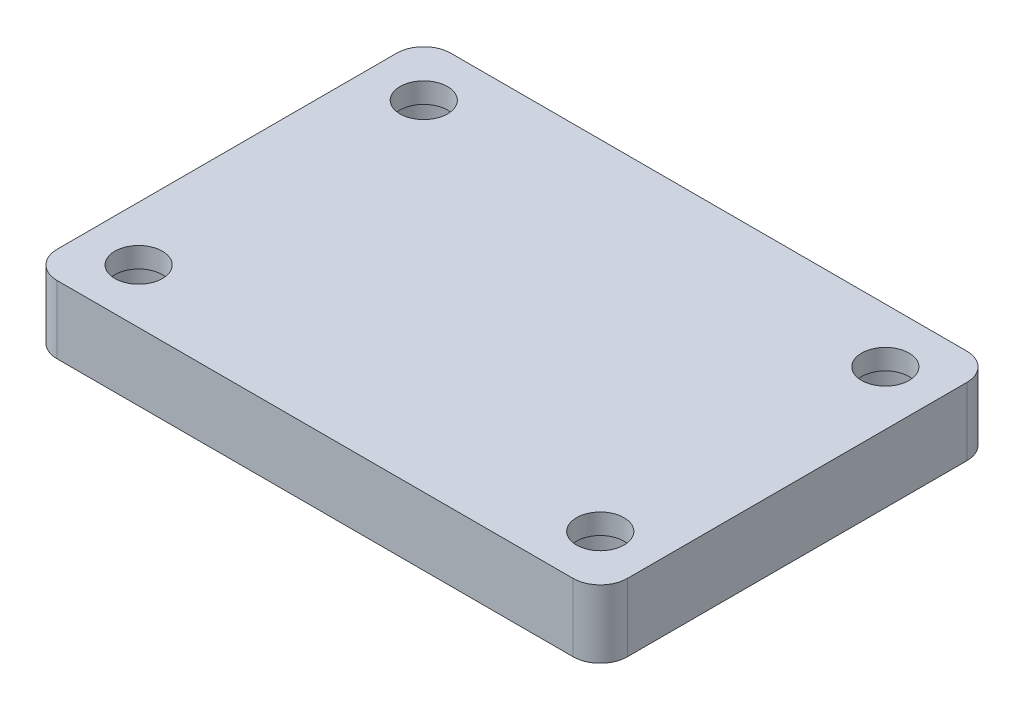
SolidWorks part; units mm, degrees
material "Plain Carbon Steel"
ref_plane "Front Plane" through (0, 0, 0) normal (0, 0, 1) x (1, 0, 0)
ref_plane "Top Plane" through (0, 0, 0) normal (0, 1, 0) x (1, 0, 0)
ref_plane "Right Plane" through (0, 0, 0) normal (1, 0, 0) x (0, 0, -1)
sketch "Sketch1" plane through (0, 0, 0) normal (0, 1, 0) x (1, 0, 0)
  line L1 (0, 0) -> (84, 0)
  line L2 (0, 0) -> (0, 58)
  line L3 (0, 58) -> (84, 58)
  line L4 (84, 0) -> (84, 58)
  dimension "Dim A" = 58
  dimension "Dim B" = 84
extrude "Extrude1" add sketch "Sketch1" along normal blind 10
hole_wizard "CBORE for M6 Hex Socket Head Cap1" positions "Sketch3" profile "Sketch2" counterbore size "M6" standard "BSI" end condition through all
sketch "Sketch3" plane through (0, 0, 0) normal (0, -1, 0) x (1, 0, 0)
  line L0 (84, 0) -> (84, -58) construction
  line L1 (84, -58) -> (0, -58) construction
  point P0 (76, -50)
  dimension "D1" = 8
  dimension "D2" = 8
sketch "Sketch2" plane through (76, 0, -50) normal (1, 0, 0) x (0, 0, -1)
  line L0 (0, 0) -> (0, 10)
  line L1 (0, 10) -> (3.5, 10)
  line L3 (3.5, 10) -> (3.5, 7)
  line L4 (3.5, 7) -> (5.5, 7)
  line L5 (5.5, 7) -> (5.5, 0)
  line L7 (5.5, 0) -> (0, 0)
  line L11 (0, -6.35) -> (0, 107.95) construction
  dimension "Thru Hole Dia." = 7
  dimension "Thru Hole Depth" = 10
  dimension "C'Bore Dia." = 11
  dimension "C'Bore Depth" = 7
pattern_linear "LPattern1" count 2 spacing 68 along (-1, 0, 0) count 2 spacing 42 along (0, 0, 1) of "CBORE for M6 Hex Socket Head Cap1"
ref_plane "Plane1" through (0, 0, -30) normal (0, 0, 1) x (1, 0, 0)
fillet "Fillet1" radius 4 4 edges at (84, 5, 0) (0, 5, 0) (0, 5, -58) (84, 5, -58)
equation "\"Dim C@LPattern1\" = \"Dim A@Sketch1\" - 16"
